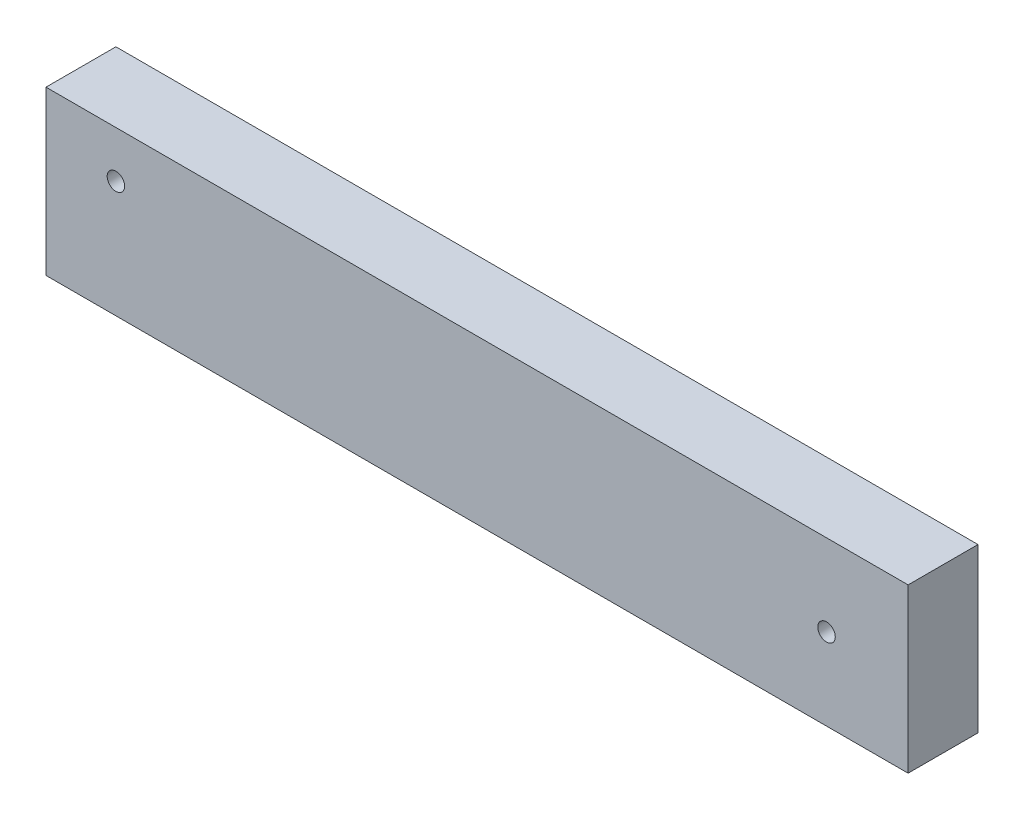
SolidWorks part; units mm, degrees
material "Oak"
ref_plane "Front" through (0, 0, 0) normal (0, 0, 1) x (1, 0, 0)
ref_plane "Top" through (0, 0, 0) normal (0, 1, 0) x (1, 0, 0)
ref_plane "Right" through (0, 0, 0) normal (1, 0, 0) x (0, 0, -1)
sketch "Sketch1" plane through (0, 0, 0) normal (0, 0, 1) x (1, 0, 0)
  line L1 (0, 0) -> (469.9, 0)
  line L2 (0, 0) -> (0, 88.9)
  line L3 (0, 88.9) -> (469.9, 88.9)
  line L4 (469.9, 0) -> (469.9, 88.9)
  dimension "D1" = 88.9
  dimension "D2" = 469.9
extrude "Boss-Extrude1" add sketch "Sketch1" along normal blind 38.1
sketch "Sketch2" plane through (0, 0, 38.1) normal (0, 0, 1) x (1, 0, 0)
  line L0 (469.9, 0) -> (469.9, 88.9) construction
  line L1 (469.9, 88.9) -> (0, 88.9) construction
  circle A0 centre (425.45, 44.45) radius 4.7625
  dimension "D3" = 9.525
  dimension "D1" = 44.45
  dimension "D2" = 44.45
extrude "Cut-Extrude1" cut sketch "Sketch2" against normal through all
sketch "Sketch3" plane through (0, 0, 38.1) normal (0, 0, 1) x (1, 0, 0)
  line L1 (469.9, 88.9) -> (0, 88.9) construction
  line L2 (469.9, 0) -> (469.9, 88.9) construction
  circle A0 centre (38.1, 63.5) radius 4.7625
  dimension "D2" = 9.525
  dimension "D1" = 431.8
  dimension "D3" = 25.4
extrude "Cut-Extrude2" cut sketch "Sketch3" against normal through all
